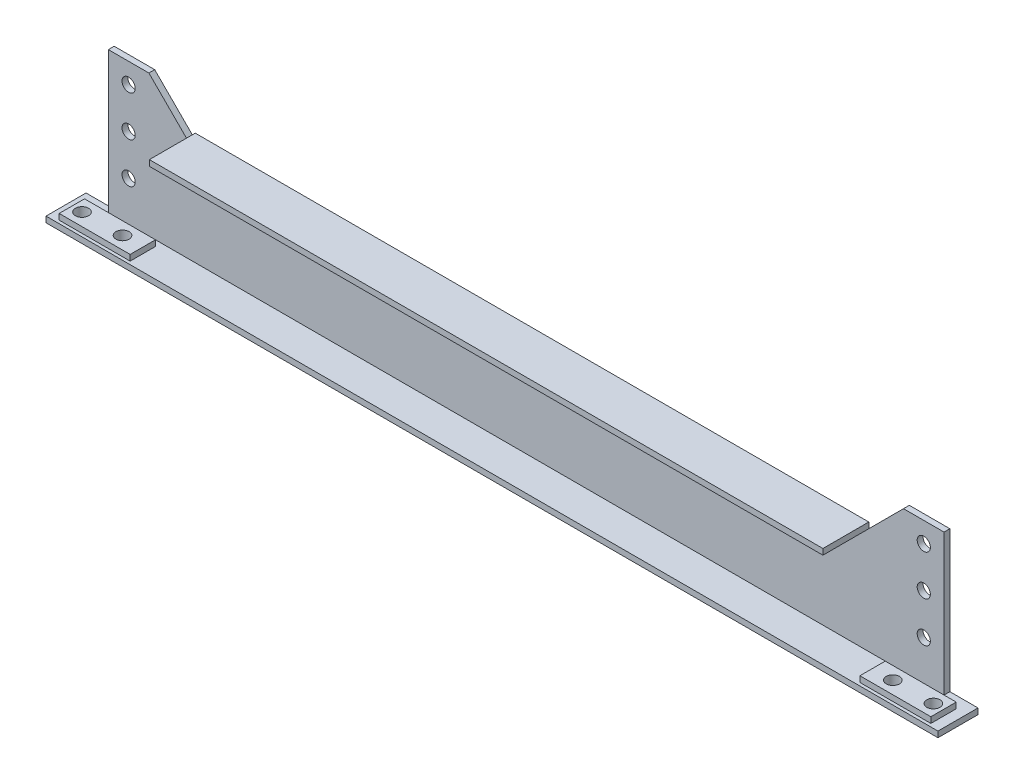
SolidWorks part; units mm, degrees
ref_plane "前视" through (0, 0, 0) normal (0, 0, 1) x (1, 0, 0)
ref_plane "上视" through (0, 0, 0) normal (0, 1, 0) x (1, 0, 0)
ref_plane "右视" through (0, 0, 0) normal (1, 0, 0) x (0, 0, -1)
sketch "草图1" plane through (0, 0, 0) normal (0, 0, 1) x (1, 0, 0)
  line L0 (0, 0) -> (1088.881, 0) construction
  line L1 (1088.881, 0) -> (-981.9373, 0) construction
  line L2 (0, 0) -> (0, 345.1364) construction
  line L3 (0, 345.1364) -> (0, -374.3029) construction
  line L4 (-744.5, 139.25) -> (-664.5, 59.25)
  line L5 (-824.5, 139.25) -> (-744.5, 139.25)
  line L6 (-824.5, 139.25) -> (-824.5, -139.25)
  line L7 (-824.5, -139.25) -> (824.5, -139.25)
  line L8 (824.5, 139.25) -> (824.5, -139.25)
  line L9 (-664.5, 59.25) -> (664.5, 59.25)
  line L10 (744.5, 139.25) -> (664.5, 59.25)
  line L11 (744.5, 139.25) -> (824.5, 139.25)
  line L12 (-784.5, 294.6321) -> (-784.5, -374.3029) construction
  circle A0 centre (-784.5, 99.25) radius 13
  circle A1 centre (-784.5, 19.25) radius 13
  circle A2 centre (-784.5, -60.75) radius 13
  circle A3 centre (784.5, -60.75) radius 13
  circle A4 centre (784.5, 19.25) radius 13
  circle A5 centre (784.5, 99.25) radius 13
  point P15 (0, 59.25)
  point P17 (0, 59.25)
  dimension "D8" = 26
  dimension "D1" = 1649
  dimension "D2" = 278.5
  dimension "D3" = 80
  dimension "D4" = 80
  dimension "D5" = 80
  dimension "D6" = 40
  dimension "D7" = 40
  dimension "D9" = 80
  dimension "D10" = 80
extrude "基体-拉伸" add sketch "草图1" along normal blind 11.5
sketch "草图2" plane through (0, 0, 11.5) normal (0, 0, 1) x (1, 0, 0)
  line L0 (0, 0) -> (0, 521.0174) construction
  line L1 (-664.5, 59.25) -> (664.5, 59.25)
  line L2 (-664.5, 59.25) -> (-664.5, 70.75)
  line L3 (-664.5, 70.75) -> (664.5, 70.75)
  line L4 (664.5, 59.25) -> (664.5, 70.75)
  dimension "D1" = 11.5
extrude "凸台-拉伸7" add sketch "草图2" along normal blind 79 and the other way through all
sketch "草图3" plane through (0, 0, 11.5) normal (0, 0, 1) x (1, 0, 0)
  line L0 (0, 567.7533) -> (0, -567.7533) construction
  line L2 (880, -139.25) -> (-880, -139.25)
  line L3 (880, -139.25) -> (880, -150.75)
  line L4 (880, -150.75) -> (-880, -150.75)
  line L5 (-880, -139.25) -> (-880, -150.75)
  line L6 (-824.5, -139.25) -> (824.5, -139.25) construction
  dimension "D1" = 1760
  dimension "D2" = 11.5
extrude "凸台-拉伸9" add sketch "草图3" along normal blind 67.5 and the other way blind 11.5
sketch "草图4" plane through (0, -139.25, 0) normal (0, 1, 0) x (-1, 0, 0)
  line L0 (-937.8047, 48) -> (1011.0707, 48) construction
  line L2 (-880, 0) -> (-824.5, 0) construction
  line L4 (0, 392.3282) -> (0, -456.8038) construction
  line L5 (-720, 23) -> (-860, 23)
  line L6 (-720, 23) -> (-720, 73)
  line L7 (-720, 73) -> (-860, 73)
  line L8 (-860, 23) -> (-860, 73)
  line L10 (720, 73) -> (860, 73)
  line L11 (860, 23) -> (860, 73)
  line L12 (720, 23) -> (860, 23)
  line L13 (720, 23) -> (720, 73)
  dimension "D1" = 48
  dimension "D2" = 50
  dimension "D3" = 720
  dimension "D4" = 140
extrude "凸台-拉伸10" add sketch "草图4" along normal blind 11.5
sketch "草图6" plane through (0, -150.75, 0) normal (0, -1, 0) x (1, 0, 0)
  line L0 (0, -191.3381) -> (0, 599.3241) construction
  line L1 (-998.2492, 48) -> (946.3524, 48) construction
  line L2 (-760, -191.3381) -> (-760, 330.6821) construction
  line L3 (-840, 330.6821) -> (-840, -191.3381) construction
  line L4 (-880, 0) -> (880, 0) construction
  circle A0 centre (-840, 48) radius 13
  circle A1 centre (-760, 48) radius 13
  circle A2 centre (760, 48) radius 13
  circle A3 centre (840, 48) radius 13
  dimension "D4" = 26
  dimension "D1" = 48
  dimension "D2" = 760
  dimension "D3" = 80
extrude "切除-拉伸1" cut sketch "草图6" against normal through all
